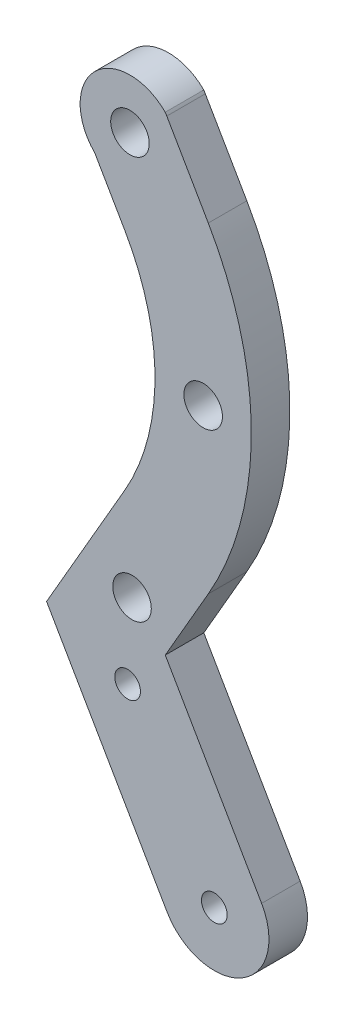
SolidWorks part; units mm, degrees
ref_plane "Front Plane" through (0, 0, 0) normal (0, 0, 1) x (1, 0, 0)
ref_plane "Top Plane" through (0, 0, 0) normal (0, 1, 0) x (1, 0, 0)
ref_plane "Right Plane" through (0, 0, 0) normal (1, 0, 0) x (0, 0, -1)
sketch "Sketch1" plane through (0, 0, 0) normal (0, 0, 1) x (1, 0, 0)
  line L0 (-82.5163, 0) -> (93.4038, 0) construction
  line L1 (0, 70.9124) -> (-2.5786, -79.7944) construction
  line L2 (-1.2133, 0) -> (31.7562, 32.9696) construction
  line L3 (-1.2133, 0) -> (30.212, -31.4253) construction
  line L4 (-1.2133, 0) -> (72.3988, 42.5) construction
  line L5 (-1.2133, 0) -> (40.9629, -24.3504) construction
  line L6 (29.0976, 17.5) -> (24.4084, 25.6218)
  line L7 (29.0976, -17.5) -> (24.4084, -25.6218)
  line L8 (42.0879, 25) -> (35.6271, 36.1905)
  line L9 (72.3988, 42.5) -> (52.8856, 31.234) construction
  line L10 (31.7562, 32.9696) -> (51.3153, 52.5286) construction
  line L11 (35.6271, 36.1905) -> (35.3897, 36.603)
  line L12 (30.212, -31.4253) -> (52.8856, -54.0989) construction
  line L13 (40.9629, -24.3504) -> (57.8482, -34.0992) construction
  line L14 (42.0879, -25) -> (35.3892, -36.6025)
  line L15 (24.4084, -25.6218) -> (16.9084, -38.6122)
  line L16 (35.3892, -36.6025) -> (50.3892, -62.5833)
  line L17 (16.9084, -38.6122) -> (33.9058, -68.0524)
  line L18 (50.3892, -62.5833) -> (29.0976, -74.876) construction
  line L19 (33.9058, -68.0524) -> (35.6584, -71.0881)
  line L20 (36.8892, -39.2006) -> (22.1584, -47.7054) construction
  arc A0 (29.0976, 17.5) -> (29.0976, -17.5) centre (-1.2133, 0) cw
  arc A1 (42.0879, 25) -> (42.0879, -25) centre (-1.2133, 0) cw
  circle A2 centre (29.5238, -43.453) radius 2
  arc A3 (50.3892, -62.5833) -> (35.6584, -71.0881) centre (43.0238, -66.8357) cw
  arc A4 (35.6271, 36.1905) -> (35.3789, 36.5922) centre (28.7695, 32.2312) ccw
  arc A5 (24.4084, 25.6218) -> (35.3789, 36.5922) centre (29.8937, 31.107) cw
  circle A6 centre (41.2867, 0) radius 3
  circle A7 centre (43.0238, -66.8357) radius 2
  circle A8 centre (30.212, -31.4253) radius 3
  circle A9 centre (29.8937, 31.107) radius 3
  dimension "D1" = 30
  dimension "D5" = 120
  dimension "D7" = 27
  dimension "D2" = 45
  dimension "D3" = 45
  dimension "D4" = 30
  dimension "D6" = 120
extrude "Boss-Extrude1" add sketch "Sketch1" along normal blind 6 contours A5 L6 A0 L7 L15 L17 L19 A3 L16 L14 A1 L8 A4 A9 A8 A7 A6 A2
